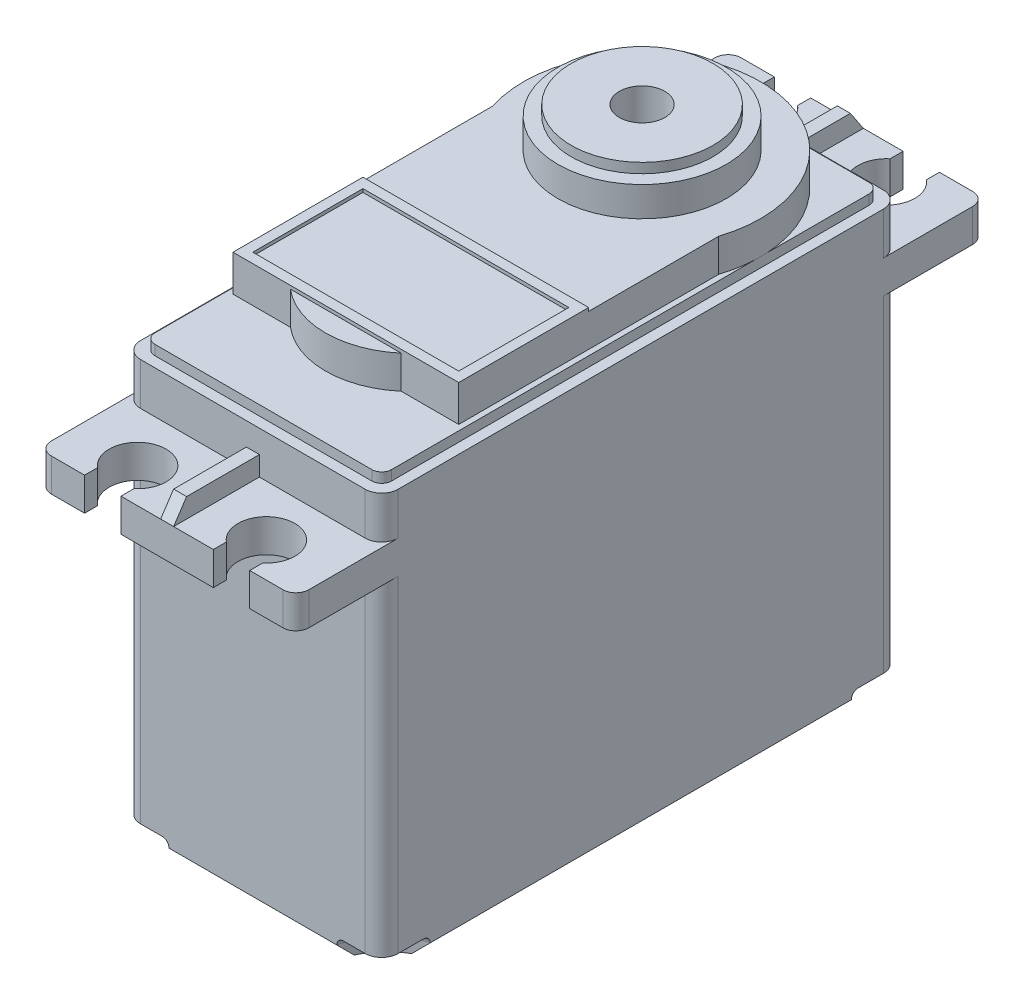
SolidWorks part; units mm, degrees
material "PBT General Purpose"
ref_plane "Front" through (0, 0, 0) normal (0, 0, 1) x (1, 0, 0)
ref_plane "Top" through (0, 0, 0) normal (0, 1, 0) x (1, 0, 0)
ref_plane "Right" through (0, 0, 0) normal (1, 0, 0) x (0, 0, -1)
sketch "Sketch1" plane through (0, 0, 0) normal (0, 1, 0) x (1, 0, 0)
  line L0 (0, 13.7537) -> (0, -13.7537) construction
  line L1 (13.7537, 0) -> (-13.7537, 0) construction
  line L2 (9.91, 19.94) -> (-9.91, 19.94)
  line L3 (-9.91, 19.94) -> (-9.91, -19.94)
  line L4 (9.91, 19.94) -> (9.91, -19.94)
  line L5 (9.91, -19.94) -> (-9.91, -19.94)
  point P6 (0, 0)
  point P8 (0, -19.94)
  point P11 (0, 19.94)
  point P12 (9.91, 0)
  point P13 (-9.91, 0)
  dimension "D1" = 19.82
  dimension "D2" = 39.88
extrude "Boss-Extrude1" add sketch "Sketch1" along normal blind 36.02
ref_plane "Plane1" through (0, 26.67, 0) normal (0, 1, 0) x (1, 0, 0)
sketch "Sketch2" plane through (0, 26.67, 0) normal (0, 1, 0) x (1, 0, 0)
  line L0 (0, 19.94) -> (0, -19.94) construction
  line L1 (9.91, 19.94) -> (-9.91, 19.94) construction
  line L2 (-9.91, -19.94) -> (9.91, -19.94) construction
  line L3 (-9.91, 19.94) -> (-9.91, 26.54)
  line L4 (9.91, 19.94) -> (9.91, 26.54)
  line L5 (-9.91, 26.54) -> (9.91, 26.54)
  line L6 (-9.91, 0) -> (9.91, 0) construction
  line L7 (-9.91, 19.94) -> (-9.91, -19.94) construction
  line L8 (9.91, -19.94) -> (9.91, 19.94) construction
  line L9 (9.91, -19.94) -> (9.91, -26.54)
  line L10 (-9.91, -19.94) -> (-9.91, -26.54)
  line L11 (-9.91, -26.54) -> (9.91, -26.54)
  line L12 (-9.91, 19.94) -> (9.91, 19.94)
  line L13 (-9.91, -19.94) -> (9.91, -19.94)
  dimension "D1" = 6.6
extrude "Boss-Extrude2" add sketch "Sketch2" along normal blind 2.54
ref_plane "Plane2" through (0, 29.21, 0) normal (0, 1, 0) x (1, 0, 0)
sketch "Sketch3" plane through (0, 29.21, 0) normal (0, 1, 0) x (1, 0, 0)
  line L0 (0, 26.54) -> (0, -26.54) construction
  line L1 (9.91, 26.54) -> (-9.91, 26.54) construction
  line L2 (-9.91, -26.54) -> (9.91, -26.54) construction
  line L3 (-4.955, 26.54) -> (-4.955, -26.54) construction
  line L4 (6.355, 26.54) -> (3.555, 26.54)
  line L5 (-6.355, 26.54) -> (-6.355, 25.5391)
  line L6 (-3.555, 26.54) -> (-3.555, 25.5391)
  line L7 (-6.355, 26.54) -> (-3.555, 26.54)
  line L8 (3.555, 26.54) -> (3.555, 25.5391)
  line L9 (6.355, 26.54) -> (6.355, 25.5391)
  arc A0 (-6.355, 25.5391) -> (-3.555, 25.5391) centre (-4.955, 23.855) ccw
  arc A1 (6.355, 25.5391) -> (3.555, 25.5391) centre (4.955, 23.855) cw
  dimension "D2" = 4.38
  dimension "D3" = 23.855
  dimension "D1" = 4.955
  dimension "D4" = 2.8
extrude "Cut-Extrude1" cut sketch "Sketch3" against normal blind 2.54
mirror "Mirror1" about plane through (0, 0, 0) normal (0, 0, 1) of "Cut-Extrude1"
ref_plane "Plane3" through (0, 29.21, 0) normal (0, 1, 0) x (1, 0, 0)
sketch "Sketch4" plane through (0, 29.21, 0) normal (0, 1, 0) x (1, 0, 0)
  line L0 (0, 26.54) -> (0, -26.54) construction
  line L1 (3.555, 26.54) -> (-3.555, 26.54) construction
  line L2 (-3.555, -26.54) -> (3.555, -26.54) construction
  line L3 (-0.5, 26.54) -> (-0.5, 19.94)
  line L4 (-9.91, 19.94) -> (9.91, 19.94) construction
  line L5 (-0.5, 19.94) -> (0.5, 19.94)
  line L6 (9.91, 19.94) -> (-9.91, 19.94) construction
  line L7 (-0.5, 26.54) -> (0.5, 26.54)
  line L8 (0.5, 26.54) -> (0.5, 19.94)
  line L9 (-9.91, 0) -> (9.91, 0) construction
  line L10 (-9.91, 19.94) -> (-9.91, -19.94) construction
  line L11 (9.91, -19.94) -> (9.91, 19.94) construction
  line L12 (0.5, -26.54) -> (0.5, -19.94)
  line L13 (-0.5, -26.54) -> (0.5, -26.54)
  line L14 (-0.5, -19.94) -> (0.5, -19.94)
  line L15 (-0.5, -26.54) -> (-0.5, -19.94)
  point P14 (0, 19.94)
  point P25 (0, -19.94)
  dimension "D1" = 1
extrude "Boss-Extrude3" add sketch "Sketch4" along normal blind 1.5
ref_plane "Plane4" through (-0.5, 0, 0) normal (-1, 0, 0) x (0, 0, 1)
sketch "Sketch5" plane through (-0.5, 0, 0) normal (-1, 0, 0) x (0, 0, 1)
  line L0 (0, 36.02) -> (0, 0) construction
  line L1 (-19.94, 36.02) -> (19.94, 36.02) construction
  line L2 (-26.54, 29.21) -> (-25.54, 30.71)
  line L3 (-26.54, 30.71) -> (-19.94, 30.71) construction
  line L4 (-25.54, 30.71) -> (-26.54, 30.71)
  line L5 (-26.54, 30.71) -> (-26.54, 29.21) construction
  line L6 (-26.54, 30.71) -> (-26.54, 29.21)
  line L7 (26.54, 30.71) -> (26.54, 29.21)
  line L8 (25.54, 30.71) -> (26.54, 30.71)
  line L9 (26.54, 29.21) -> (25.54, 30.71)
  dimension "D1" = 1
extrude "Cut-Extrude2" cut sketch "Sketch5" against normal up to surface (1 mm away) up to face at (0.5, 29.96, -23.24)
ref_plane "Plane5" through (0, 36.02, 0) normal (0, 1, 0) x (1, 0, 0)
sketch "Sketch6" plane through (0, 36.02, 0) normal (0, 1, 0) x (1, 0, 0)
  line L0 (-9.91, 19.94) -> (-9.91, -19.94)
  line L1 (-9.91, -19.94) -> (9.91, -19.94)
  line L2 (9.91, -19.94) -> (9.91, 19.94) construction
  line L3 (-9.91, -19.94) -> (9.91, -19.94) construction
  line L4 (9.91, -19.94) -> (9.91, 19.94)
  line L5 (9.91, 19.94) -> (-9.91, 19.94)
extrude "Cut-Extrude3" cut sketch "Sketch6" against normal blind 3.55
ref_plane "Plane6" through (0, 32.47, 0) normal (0, 1, 0) x (1, 0, 0)
sketch "Sketch7" plane through (0, 32.47, 0) normal (0, 1, 0) x (1, 0, 0)
  line L0 (0, 19.94) -> (0, -19.94) construction
  line L1 (9.91, 19.94) -> (-9.91, 19.94) construction
  line L2 (-9.91, -19.94) -> (9.91, -19.94) construction
  line L3 (-9.91, 0) -> (9.91, 0) construction
  line L4 (-9.91, 19.94) -> (-9.91, -19.94) construction
  line L5 (9.91, -19.94) -> (9.91, 19.94) construction
  line L6 (-9.11, 19.136) -> (-9.11, -19.136)
  line L7 (9.11, 19.136) -> (9.11, -19.136)
  line L8 (-9.11, 19.136) -> (9.11, 19.136)
  line L9 (-9.11, -19.136) -> (9.11, -19.136)
  point P15 (-9.11, 0)
  point P18 (9.11, 0)
  dimension "D1" = 19.136
  dimension "D2" = 18.22
extrude "Boss-Extrude4" add sketch "Sketch7" along normal blind 0.762
fillet "Fillet1" radius 1.27 8 edges
fillet "Fillet2" radius 0.762 4 edges at (9.11, 32.851, -19.136) (-9.11, 32.851, -19.136) (-9.11, 32.851, 19.136) (9.11, 32.851, 19.136)
ref_plane "Plane7" through (0, 33.232, 0) normal (0, 1, 0) x (1, 0, 0)
sketch "Sketch8" plane through (0, 33.232, 0) normal (0, 1, 0) x (1, 0, 0)
  line L0 (0, 19.136) -> (0, -19.136) construction
  line L1 (8.348, 19.136) -> (-8.348, 19.136) construction
  line L2 (-8.348, -19.136) -> (8.348, -19.136) construction
  line L3 (8.6857, 7.214) -> (8.6857, -12.786)
  line L4 (-8.348, -19.136) -> (8.348, -19.136) construction
  line L6 (-8.6857, 7.214) -> (-8.6857, -12.786)
  line L7 (-8.6857, -12.786) -> (8.6857, -12.786)
  arc A0 (8.6857, 7.214) -> (-8.6857, 7.214) centre (0, 10.011) ccw
  point P2 (0, 19.136)
  dimension "D1" = 18.25
  dimension "D2" = 20
  dimension "D3" = 6.35
extrude "Boss-Extrude5" add sketch "Sketch8" along normal blind 2.54
ref_plane "Plane8" through (0, 35.772, 0) normal (0, 1, 0) x (1, 0, 0)
sketch "Sketch10" plane through (0, 35.772, 0) normal (0, 1, 0) x (1, 0, 0)
  line L0 (0, 19.136) -> (0, -12.786) construction
  line L1 (-8.6857, -12.786) -> (8.6857, -12.786) construction
  arc A0 (8.6857, 7.214) -> (-8.6857, 7.214) centre (0, 10.011) ccw construction
  circle A1 centre (0, 10.011) radius 6.477
  dimension "D1" = 12.954
extrude "Boss-Extrude6" add sketch "Sketch10" along normal blind 2.286
sketch "Sketch11" plane through (0, 38.058, 0) normal (0, 1, 0) x (1, 0, 0)
  circle A0 centre (0, 10.011) radius 5.461
  dimension "D1" = 10.922
extrude "Boss-Extrude7" add sketch "Sketch11" along normal blind 0.762
sketch "Sketch12" plane through (0, 38.82, 0) normal (0, 1, 0) x (1, 0, 0)
  circle A0 centre (0, 10.011) radius 1.75
  dimension "D1" = 3.5
extrude "Cut-Extrude4" cut sketch "Sketch12" against normal blind 2.54
sketch "Sketch13" plane through (0, 35.772, 0) normal (0, 1, 0) x (1, 0, 0)
  line L0 (-8.6857, -12.786) -> (-8.6857, -2.786)
  line L1 (-8.6857, 7.214) -> (-8.6857, -12.786) construction
  line L2 (-8.6857, -2.786) -> (8.6857, -2.786)
  line L3 (8.6857, -12.786) -> (8.6857, 7.214) construction
  line L4 (8.6857, -2.786) -> (8.6857, -12.786)
  line L5 (8.6857, -12.786) -> (-8.6857, -12.786)
  line L6 (0, -2.786) -> (0, -12.786) construction
  line L7 (-8.6857, -7.786) -> (8.6857, -7.786) construction
  line L8 (-7.9237, -3.548) -> (-7.9237, -12.024)
  line L9 (-7.9237, -3.548) -> (7.9237, -3.548)
  line L10 (-7.9237, -12.024) -> (7.9237, -12.024)
  line L11 (7.9237, -3.548) -> (7.9237, -12.024)
  point P18 (-7.9237, -7.786)
  point P20 (0, -12.024)
  point P21 (0, -3.548)
  dimension "D1" = 0.762
  dimension "D2" = 0.762
extrude "Boss-Extrude8" add sketch "Sketch13" along normal blind 0.254
ref_plane "Plane9" through (0, 33.232, 0) normal (0, 1, 0) x (1, 0, 0)
sketch "Sketch14" plane through (0, 33.232, 0) normal (0, 1, 0) x (1, 0, 0)
  line L0 (0, -12.786) -> (0, -19.136) construction
  line L1 (-8.6857, -12.786) -> (8.6857, -12.786) construction
  line L2 (-8.348, -19.136) -> (8.348, -19.136) construction
  line L3 (-7.9237, -7.786) -> (7.9237, -7.786) construction
  line L4 (-7.9237, -3.548) -> (-7.9237, -12.024) construction
  line L5 (7.9237, -12.024) -> (7.9237, -3.548) construction
  line L6 (-4.2604, -12.786) -> (4.2604, -12.786)
  arc A0 (-4.2604, -12.786) -> (4.2604, -12.786) centre (0, -7.786) ccw
  dimension "D2" = 6.5689
  dimension "D1" = 12.786
extrude "Boss-Extrude9" add sketch "Sketch14" along normal blind 2.54
ref_plane "Plane10" through (0, 0, 0) normal (0, -1, 0) x (-1, 0, 0)
sketch "Sketch15" plane through (0, 0, 0) normal (0, -1, 0) x (-1, 0, 0)
  line L0 (0, -19.94) -> (0, 19.94) construction
  line L1 (-8.64, -19.94) -> (8.64, -19.94) construction
  line L2 (-8.64, 19.94) -> (8.64, 19.94) construction
  line L3 (9.91, 0) -> (-9.91, 0) construction
  line L4 (9.91, 18.67) -> (9.91, -18.67) construction
  line L5 (-9.91, -18.67) -> (-9.91, 18.67) construction
  line L6 (6.4637, -19.94) -> (9.91, -19.94)
  line L7 (9.91, -18.67) -> (9.91, -26.54) construction
  line L8 (9.91, -19.94) -> (9.91, -16.2118)
  line L9 (-9.91, -19.94) -> (-9.91, -16.2118)
  line L10 (-6.4637, -19.94) -> (-9.91, -19.94)
  line L11 (-6.4637, 19.94) -> (-9.91, 19.94)
  line L12 (-9.91, 19.94) -> (-9.91, 16.2118)
  line L13 (9.91, 19.94) -> (9.91, 16.2118)
  line L14 (6.4637, 19.94) -> (9.91, 19.94)
  arc A0 (9.91, -16.2118) -> (6.4637, -19.94) centre (11.35, -21) ccw
  arc A1 (-9.91, -16.2118) -> (-6.4637, -19.94) centre (-11.35, -21) cw
  arc A2 (-9.91, 16.2118) -> (-6.4637, 19.94) centre (-11.35, 21) ccw
  arc A3 (9.91, 16.2118) -> (6.4637, 19.94) centre (11.35, 21) cw
  dimension "D3" = 10
  dimension "D1" = 11.35
  dimension "D2" = 21
  dimension "D4" = 3.4463
extrude "Cut-Extrude5" cut sketch "Sketch15" against normal blind 1.524
sketch "Sketch16" plane through (0, 0, 0) normal (0, -1, 0) x (-1, 0, 0)
  line L0 (0, -19.94) -> (0, 19.94) construction
  line L1 (6.4637, -19.94) -> (-6.4637, -19.94) construction
  line L2 (8.64, 19.94) -> (-8.64, 19.94) construction
  line L3 (9.91, 0) -> (-9.91, 0) construction
  line L4 (9.91, 16.2118) -> (9.91, -16.2118) construction
  line L5 (-9.91, -16.2118) -> (-9.91, 16.2118) construction
  circle A0 centre (8.64, -18.67) radius 0.5
  circle A1 centre (-8.64, -18.67) radius 0.5
  circle A2 centre (-8.64, 18.67) radius 0.5
  circle A3 centre (8.64, 18.67) radius 0.5
  dimension "D1" = 1
extrude "Cut-Extrude6" cut sketch "Sketch16" against normal blind 6
chamfer "Chamfer1" distance 1 angle 45 4 edges at (0, 0, -19.94) (9.91, 0, 0) (0, 0, 19.94) (-9.91, 0, 0)
fillet "Fillet3" radius 0.5 4 edges at (-7.6784, 1.524, 17.606) (7.6784, 1.524, 17.606) (7.6784, 1.524, -17.606) (-7.6784, 1.524, -17.606)
ref_plane "Plane13" through (0, 0, -19.94) normal (0, 0, -1) x (-1, 0, 0)
sketch "Sketch17" plane through (0, 0, -19.94) normal (0, 0, -1) x (-1, 0, 0)
  line L0 (0, 1) -> (0, 26.67) construction
  line L1 (-6.4637, 1) -> (6.4637, 1) construction
  line L2 (-3.555, 26.67) -> (3.555, 26.67) construction
  line L3 (-3.175, 1) -> (-3.175, 4.81)
  line L4 (-3.175, 4.81) -> (3.175, 4.81)
  line L5 (3.175, 1) -> (3.175, 4.81)
  line L6 (-3.175, 1) -> (3.175, 1)
  line L7 (0, 1.5) -> (-2.675, 1.5)
  line L8 (-2.675, 1.5) -> (-2.675, 4.31)
  line L9 (-2.675, 4.31) -> (0, 4.31)
  line L10 (0, 1.5) -> (2.675, 1.5)
  line L11 (2.675, 1.5) -> (2.675, 4.31)
  line L12 (2.675, 4.31) -> (0, 4.31)
  point P11 (0, 4.81)
  dimension "D1" = 6.35
  dimension "D2" = 3.81
  dimension "D4" = 0.5
  dimension "D5" = 0.5
  dimension "D6" = 0.5
extrude "Boss-Extrude10" add sketch "Sketch17" along normal blind 1.5
fillet "Fillet5" radius 0.5 4 edges at (-3.175, 4.81, -20.69) (-3.175, 1, -20.69) (3.175, 1, -20.69) (3.175, 4.81, -20.69)
fillet "Fillet6" radius 1 4 edges at (9.91, 27.94, 26.54) (9.91, 27.94, -26.54) (-9.91, 27.94, 26.54) (-9.91, 27.94, -26.54)
